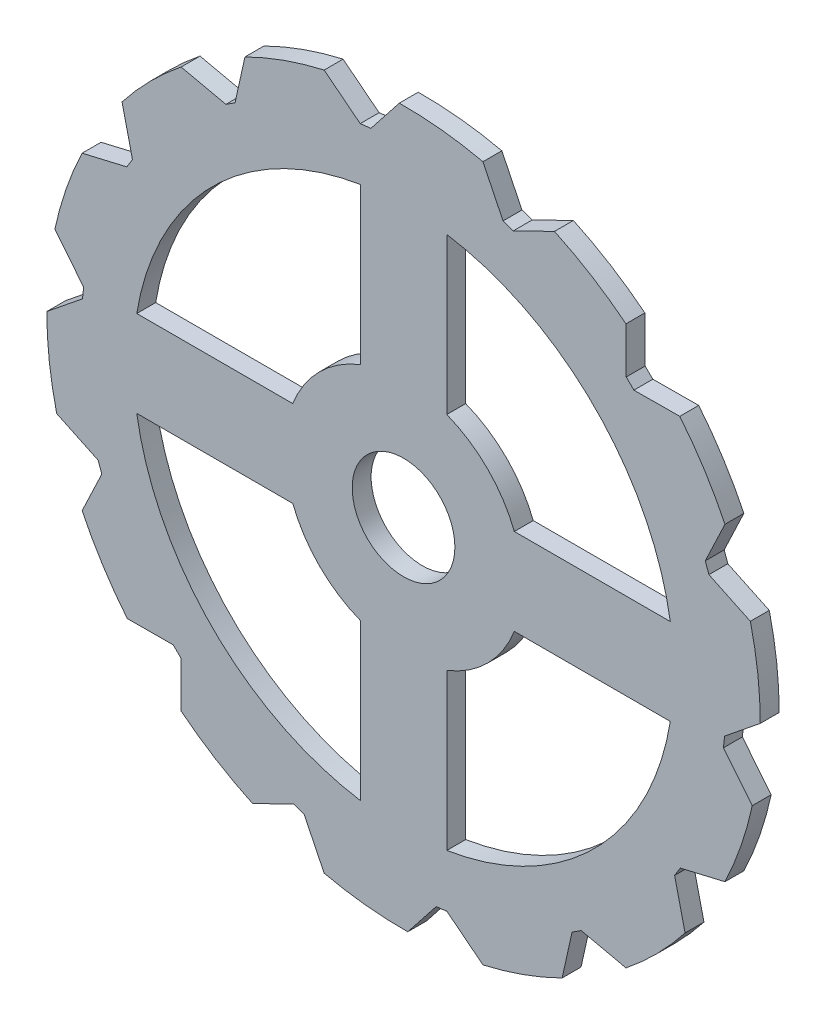
SolidWorks part; units mm, degrees
ref_plane "Front Plane" through (0, 0, 0) normal (0, 0, 1) x (1, 0, 0)
ref_plane "Top Plane" through (0, 0, 0) normal (0, 1, 0) x (1, 0, 0)
ref_plane "Right Plane" through (0, 0, 0) normal (1, 0, 0) x (0, 0, -1)
sketch "Sketch1" plane through (0, 0, 0) normal (0, 0, 1) x (1, 0, 0)
  line L0 (-24.6779, -4) -> (-10.247, -4)
  line L1 (-24.6779, 4) -> (-10.247, 4)
  line L2 (0, -41.7572) -> (0, 51.4062) construction
  line L3 (4, 24.6779) -> (4, 10.247)
  line L4 (-4, 24.6779) -> (-4, 10.247)
  line L5 (24.6779, -4) -> (10.247, -4)
  line L6 (24.6779, 4) -> (10.247, 4)
  line L7 (-4, -24.6779) -> (-4, -10.247)
  line L8 (4, -24.6779) -> (4, -10.247)
  line L9 (-46.1658, 0) -> (64.7153, 0) construction
  line L10 (-33, 0) -> (-29.6987, 2.6649)
  line L11 (-29.6987, 2.6649) -> (-29.5927, 3.6593)
  line L12 (-29.5927, 3.6593) -> (-32.2576, 6.9605)
  line L13 (-33, 0) -> (-32.2576, 6.9605) construction
  line L14 (-25.0744, 16.1367) -> (-26.043, 20.2672)
  line L15 (-25.6014, 15.2868) -> (-25.0744, 16.1367)
  line L16 (-29.732, 14.3182) -> (-25.6014, 15.2868)
  line L17 (-15.5898, 25.418) -> (-14.6703, 29.5598)
  line L18 (-16.4334, 24.8809) -> (-15.5898, 25.418)
  line L19 (-20.5752, 25.8004) -> (-16.4334, 24.8809)
  line L20 (-3.0175, 29.665) -> (-0.392, 32.9977)
  line L21 (-4.0105, 29.5471) -> (-3.0175, 29.665)
  line L22 (-7.3432, 32.1726) -> (-4.0105, 29.5471)
  line L23 (10.1525, 28.0365) -> (13.964, 29.9)
  line L24 (9.2067, 28.3611) -> (10.1525, 28.0365)
  line L25 (7.3432, 32.1726) -> (9.2067, 28.3611)
  line L26 (21.3117, 20.855) -> (25.5542, 20.8802)
  line L27 (20.6004, 21.5579) -> (21.3117, 20.855)
  line L28 (20.5752, 25.8004) -> (20.6004, 21.5579)
  line L29 (28.2498, 9.5429) -> (32.0831, 7.7248)
  line L30 (27.9139, 10.4848) -> (28.2498, 9.5429)
  line L31 (29.732, 14.3182) -> (27.9139, 10.4848)
  line L32 (29.5927, -3.6593) -> (32.2576, -6.9605)
  line L33 (29.6987, -2.6649) -> (29.5927, -3.6593)
  line L34 (33, 0) -> (29.6987, -2.6649)
  line L35 (25.0744, -16.1367) -> (26.043, -20.2672)
  line L36 (25.6014, -15.2868) -> (25.0744, -16.1367)
  line L37 (29.732, -14.3182) -> (25.6014, -15.2868)
  line L38 (15.5898, -25.418) -> (14.6703, -29.5598)
  line L39 (16.4334, -24.8809) -> (15.5898, -25.418)
  line L40 (20.5752, -25.8004) -> (16.4334, -24.8809)
  line L41 (3.0175, -29.665) -> (0.392, -32.9977)
  line L42 (4.0105, -29.5471) -> (3.0175, -29.665)
  line L43 (7.3432, -32.1726) -> (4.0105, -29.5471)
  line L44 (-10.1525, -28.0365) -> (-13.964, -29.9)
  line L45 (-9.2067, -28.3611) -> (-10.1525, -28.0365)
  line L46 (-7.3432, -32.1726) -> (-9.2067, -28.3611)
  line L47 (-21.3117, -20.855) -> (-25.5542, -20.8802)
  line L48 (-20.6004, -21.5579) -> (-21.3117, -20.855)
  line L49 (-20.5752, -25.8004) -> (-20.6004, -21.5579)
  line L50 (-28.2498, -9.5429) -> (-32.0831, -7.7248)
  line L51 (-27.9139, -10.4848) -> (-28.2498, -9.5429)
  line L52 (-29.732, -14.3182) -> (-27.9139, -10.4848)
  circle A0 centre (0, 0) radius 25
  circle A1 centre (0, 0) radius 11
  circle A2 centre (0, 0) radius 33
  circle A3 centre (0, 0) radius 4.75
  point P33 (-33, 0)
  point P37 (-29.732, 14.3182)
  point P42 (-20.5752, 25.8004)
  point P47 (-7.3432, 32.1726)
  point P52 (7.3432, 32.1726)
  point P57 (20.5752, 25.8004)
  point P62 (29.732, 14.3182)
  point P67 (33, 0)
  point P72 (29.732, -14.3182)
  point P77 (20.5752, -25.8004)
  point P82 (7.3432, -32.1726)
  point P87 (-7.3432, -32.1726)
  point P92 (-20.5752, -25.8004)
  point P97 (-29.732, -14.3182)
  dimension "D3" = 50
  dimension "D5" = 66
  dimension "D6" = 22
  dimension "D7" = 45
  dimension "D9" = 3
  dimension "D12" = 9.5
  dimension "D2" = 8
  dimension "D4" = 4
  dimension "D8" = 45
  dimension "D10" = 1
  dimension "D1" = 4
  dimension "D11" = 14
extrude "Boss-Extrude1" add sketch "Sketch1" along normal blind 1.75 contours L34 A2 L29 L30 L31 L26 L27 L28 L23 L24 L25 L20 L21 L22 L17 L18 L19 L14 L15 L16 L12 L11 L10 L50 L51 L52 L47 L48 L49 L44 L45 L46 L41 L42 L43 L38 L39 L40 L35 | A1 L3 A0 L4 | A1 L5 A0 L6 | A1 L7 A0 L8 | A1 L1 A0 L0 | A1 A3
